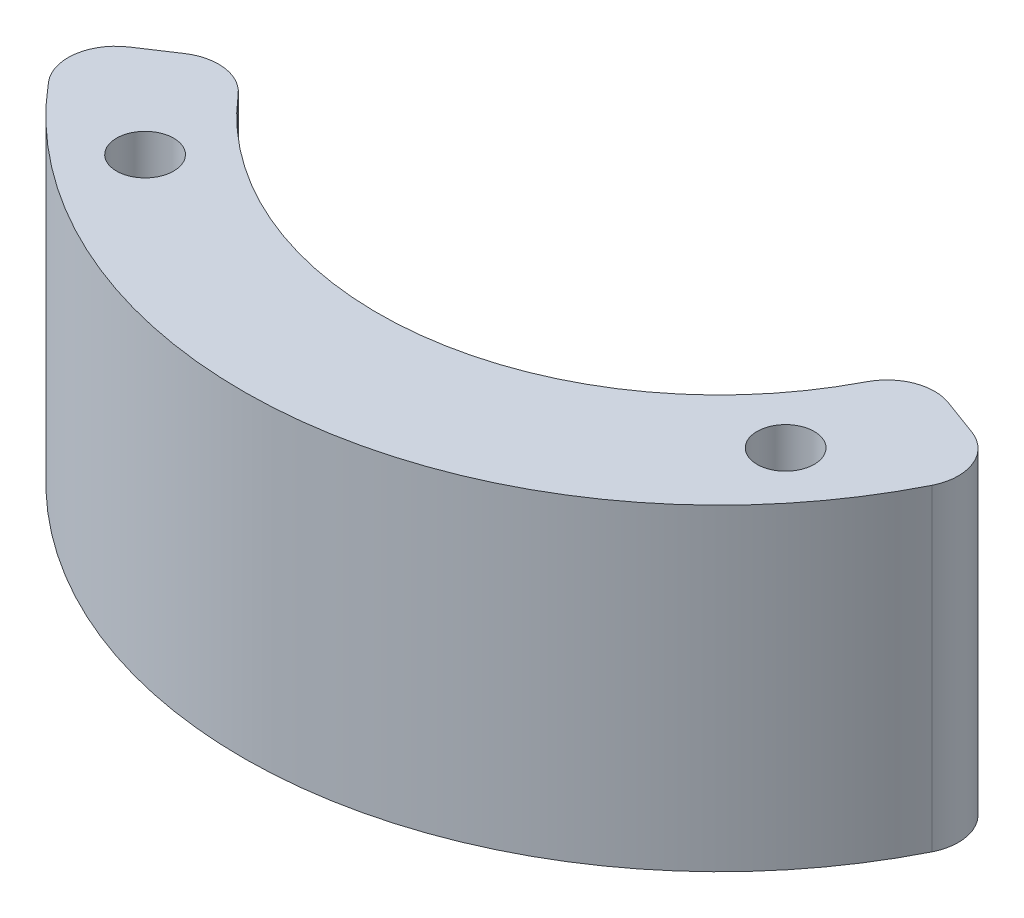
SolidWorks part; units mm, degrees
ref_plane "Front Plane" through (0, 0, 0) normal (0, 0, 1) x (1, 0, 0)
ref_plane "Top Plane" through (0, 0, 0) normal (0, 1, 0) x (1, 0, 0)
ref_plane "Right Plane" through (0, 0, 0) normal (1, 0, 0) x (0, 0, -1)
sketch "Sketch1" plane through (0, 0, 0) normal (0, 1, 0) x (1, 0, 0)
  line L0 (-25.018, -16.556) -> (-17.9295, -11.8651)
  line L1 (20.1758, -7.4288) -> (28.1523, -10.3658)
  circle A0 centre (0, 0) radius 30 construction
  circle A1 centre (0, 0) radius 21.5 construction
  circle A2 centre (0, 0) radius 25.75 construction
  circle A3 centre (-20.1758, 16) radius 1.8 construction
  arc A7 (-25.018, -16.556) -> (28.1523, -10.3658) centre (0, 0) ccw
  arc A8 (-17.9295, -11.8651) -> (20.1758, -7.4288) centre (0, 0) ccw
  circle A9 centre (16, 20.1758) radius 1.8 construction
  circle A10 centre (20.1758, -16) radius 1.8
  circle A11 centre (-16, -20.1758) radius 1.8
  point P16 (0.0075, 0.0203)
  point P23 (0, 0)
  dimension "D1" = 60
  dimension "D2" = 43
  dimension "D3" = 51.5
  dimension "D4" = 3.6
  dimension "D5" = 16
  dimension "D6" = 4
extrude "Boss-Extrude1" add sketch "Sketch1" along normal blind 20
fillet "Fillet1" radius 3 4 edges at (28.1523, 10, 10.3658) (20.1758, 10, 7.4288) (-17.9295, 10, 11.8651) (-25.018, 10, 16.556)
